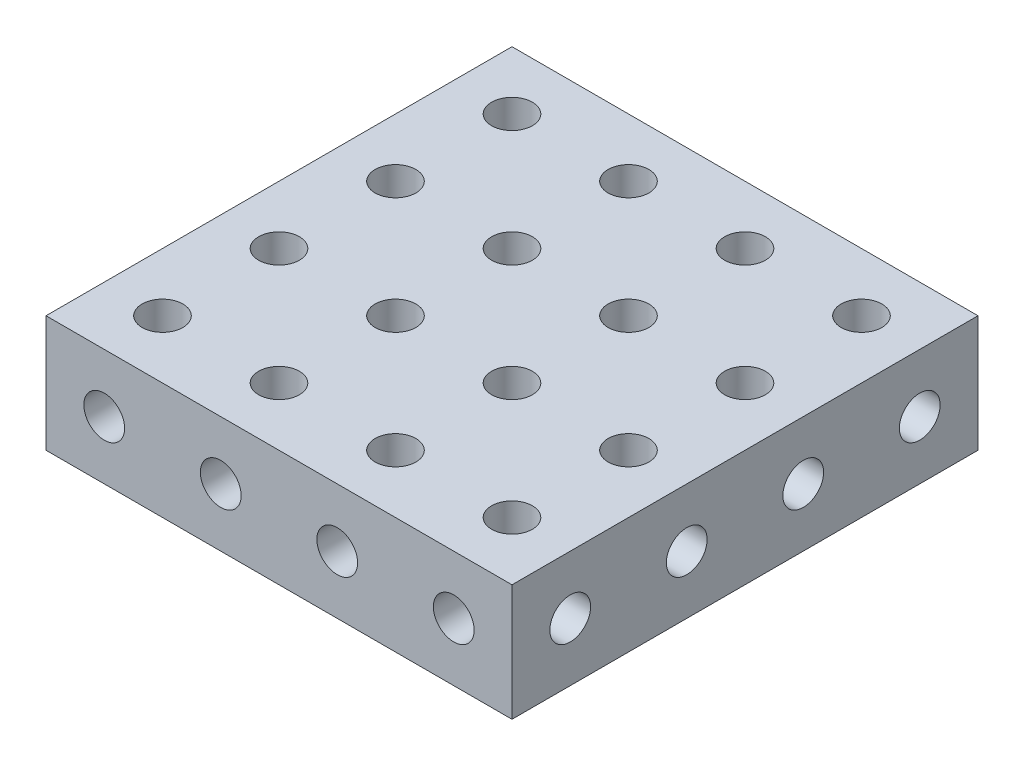
SolidWorks part; units mm, degrees
ref_plane "Plan de face" through (0, 0, 0) normal (0, 0, 1) x (1, 0, 0)
ref_plane "Plan de dessus" through (0, 0, 0) normal (0, 1, 0) x (1, 0, 0)
ref_plane "Plan de droite" through (0, 0, 0) normal (1, 0, 0) x (0, 0, -1)
sketch "Esquisse1" plane through (0, 0, 0) normal (1, 0, 0) x (0, 0, -1)
  line L1 (0, 0) -> (40, 0)
  line L2 (0, 0) -> (0, 10)
  line L3 (0, 10) -> (40, 10)
  line L4 (40, 0) -> (40, 10)
  dimension "D1" = 40
  dimension "D2" = 10
extrude "Boss.-Extru.1" add sketch "Esquisse1" along normal blind 40
sketch "Esquisse2" plane through (0, 10, 0) normal (0, 1, 0) x (1, 0, 0)
  line L0 (0, 35) -> (40, 35) construction
  line L4 (40, 40) -> (0, 40) construction
  circle A0 centre (5, 35) radius 1.75
  circle A1 centre (15, 35) radius 1.75
  circle A2 centre (25, 35) radius 1.75
  circle A3 centre (35, 35) radius 1.75
  circle A4 centre (5, 25) radius 1.75
  circle A5 centre (15, 25) radius 1.75
  circle A6 centre (25, 25) radius 1.75
  circle A7 centre (35, 25) radius 1.75
  circle A8 centre (5, 15) radius 1.75
  circle A9 centre (15, 15) radius 1.75
  circle A10 centre (25, 15) radius 1.75
  circle A11 centre (35, 15) radius 1.75
  circle A12 centre (5, 5) radius 1.75
  circle A13 centre (15, 5) radius 1.75
  circle A14 centre (25, 5) radius 1.75
  circle A15 centre (35, 5) radius 1.75
  dimension "D4" = 3.5
  dimension "D1" = 5
  dimension "D2" = 10
  dimension "D3" = 10
  dimension "D5" = 10
  dimension "D6" = 5
  dimension "D7" = 4
extrude "Enlèv. mat.-Extru.1" cut sketch "Esquisse2" against normal through all
sketch "Esquisse3" plane through (0, 0, 0) normal (0, 0, 1) x (1, 0, 0)
  line L0 (0, 5) -> (40, 5) construction
  line L1 (0, 10) -> (0, 0) construction
  line L2 (40, 10) -> (40, 0) construction
  circle A0 centre (5, 5) radius 1.75
  circle A1 centre (15, 5) radius 1.75
  circle A2 centre (25, 5) radius 1.75
  circle A3 centre (35, 5) radius 1.75
  dimension "D4" = 3.5
  dimension "D1" = 5
  dimension "D2" = 10
  dimension "D3" = 10
  dimension "D5" = 10
extrude "Enlèv. mat.-Extru.2" cut sketch "Esquisse3" against normal blind 40
sketch "Esquisse4" plane through (40, 0, 0) normal (1, 0, 0) x (0, 0, -1)
  line L0 (0, 5) -> (40, 5) construction
  line L1 (0, 10) -> (0, 0) construction
  line L2 (40, 0) -> (40, 10) construction
  circle A0 centre (5, 5) radius 1.75
  circle A1 centre (15, 5) radius 1.75
  circle A2 centre (25, 5) radius 1.75
  circle A3 centre (35, 5) radius 1.75
  dimension "D1" = 3.5
  dimension "D2" = 5
  dimension "D3" = 4
extrude "Enlèv. mat.-Extru.3" cut sketch "Esquisse4" against normal blind 40
